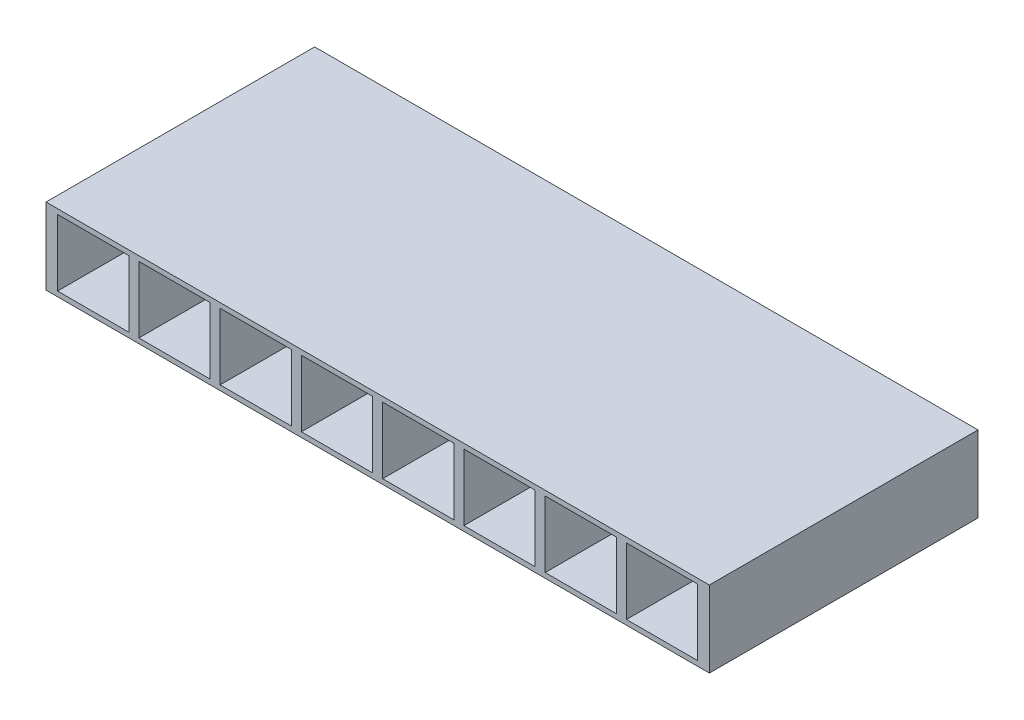
SolidWorks part; units mm, degrees
ref_plane "Plan de face" through (0, 0, 0) normal (0, 0, 1) x (1, 0, 0)
ref_plane "Plan de dessus" through (0, 0, 0) normal (0, 1, 0) x (1, 0, 0)
ref_plane "Plan de droite" through (0, 0, 0) normal (1, 0, 0) x (0, 0, -1)
sketch "Esquisse1" plane through (0, 0, 0) normal (0, 0, 1) x (1, 0, 0)
  line L0 (-2.55, -1) -> (-2.55, 1)
  line L1 (-7.5, -1.15) -> (12.5, -1.15)
  line L2 (-7.5, -1.15) -> (-7.5, 1.15)
  line L3 (-7.5, 1.15) -> (12.5, 1.15)
  line L4 (12.5, -1.15) -> (12.5, 1.15)
  line L5 (-7.5, -1.15) -> (-5, -0.7667) construction
  line L6 (-7.5, 1.15) -> (-5, 0.7667) construction
  line L7 (-7.15, -1) -> (-5, -1)
  line L8 (-7.15, -1) -> (-7.15, 1)
  line L9 (-7.15, 1) -> (-5, 1)
  line L10 (-5, -1) -> (-5, 1)
  line L11 (-7.15, -1) -> (-5, 1) construction
  line L12 (-7.15, 1) -> (-5, -1) construction
  line L13 (-4.7, -1) -> (-4.7, 1)
  line L14 (-4.7, 1) -> (-2.55, 1)
  line L15 (-4.7, -1) -> (-2.55, -1)
  line L16 (-0.1, -1) -> (-0.1, 1)
  line L17 (-2.25, -1) -> (-2.25, 1)
  line L18 (-2.25, 1) -> (-0.1, 1)
  line L19 (-2.25, -1) -> (-0.1, -1)
  line L20 (2.35, -1) -> (2.35, 1)
  line L21 (0.2, -1) -> (0.2, 1)
  line L22 (0.2, 1) -> (2.35, 1)
  line L23 (0.2, -1) -> (2.35, -1)
  line L24 (4.8, -1) -> (4.8, 1)
  line L25 (2.65, -1) -> (2.65, 1)
  line L26 (2.65, 1) -> (4.8, 1)
  line L27 (2.65, -1) -> (4.8, -1)
  line L28 (7.25, -1) -> (7.25, 1)
  line L29 (5.1, -1) -> (5.1, 1)
  line L30 (5.1, 1) -> (7.25, 1)
  line L31 (5.1, -1) -> (7.25, -1)
  line L32 (9.7, -1) -> (9.7, 1)
  line L33 (7.55, -1) -> (7.55, 1)
  line L34 (7.55, 1) -> (9.7, 1)
  line L35 (7.55, -1) -> (9.7, -1)
  line L36 (12.15, -1) -> (12.15, 1)
  line L37 (10, -1) -> (10, 1)
  line L38 (10, 1) -> (12.15, 1)
  line L39 (10, -1) -> (12.15, -1)
  point P0 (0, 0)
  point P6 (-6.075, 0)
  dimension "D1" = 20
  dimension "D2" = 2.3
  dimension "D3" = 2
  dimension "D4" = 2.15
  dimension "D5" = 0.35
  dimension "D6" = 8
extrude "Boss.-Extru.2" add sketch "Esquisse1" along normal blind 8.1
